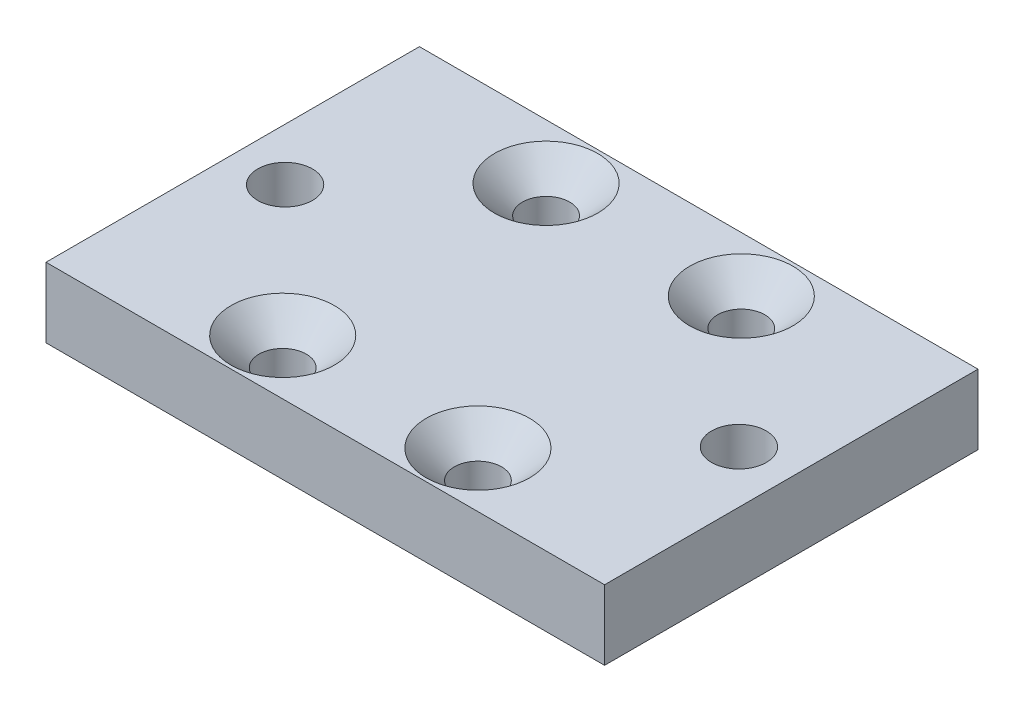
SolidWorks part; units mm, degrees
ref_plane "Front Plane" through (0, 0, 0) normal (0, 0, 1) x (1, 0, 0)
ref_plane "Top Plane" through (0, 0, 0) normal (0, 1, 0) x (1, 0, 0)
ref_plane "Right Plane" through (0, 0, 0) normal (1, 0, 0) x (0, 0, -1)
sketch "Sketch1" plane through (0, 0, 0) normal (0, 1, 0) x (1, 0, 0)
  line L1 (0, 0) -> (50.8, 0)
  line L2 (0, 0) -> (0, 33.9598)
  line L3 (0, 33.9598) -> (50.8, 33.9598)
  line L4 (50.8, 0) -> (50.8, 33.9598)
  dimension "D1" = 33.9598
  dimension "D2" = 50.8
extrude "Boss-Extrude1" add sketch "Sketch1" along normal blind 6.35
sketch "Sketch2" plane through (0, 6.35, 0) normal (0, 1, 0) x (1, 0, 0)
  line L0 (16.5227, 28.956) -> (0, 28.956) construction
  line L1 (0, 33.9598) -> (0, 0) construction
  line L2 (16.5227, 5.0038) -> (0, 5.0038) construction
  line L3 (16.5227, 5.0038) -> (16.5227, 0) construction
  line L4 (0, 0) -> (50.8, 0) construction
  line L5 (16.5227, 28.956) -> (16.5227, 33.9598) construction
  line L6 (50.8, 33.9598) -> (0, 33.9598) construction
  line L7 (34.2773, 28.956) -> (34.2773, 33.9598) construction
  line L8 (34.2773, 28.956) -> (50.8, 28.956) construction
  line L9 (50.8, 0) -> (50.8, 33.9598) construction
  line L10 (34.2773, 5.0038) -> (50.8, 5.0038) construction
  line L11 (34.2773, 5.0038) -> (34.2773, 0) construction
  line L12 (16.5227, 27.051) -> (16.5227, 6.9088) construction
  line L13 (32.3723, 28.956) -> (18.4277, 28.956) construction
  circle A0 centre (16.5227, 28.956) radius 1.905
  circle A1 centre (16.5227, 5.0038) radius 1.905
  circle A2 centre (34.2773, 28.956) radius 1.905
  circle A3 centre (34.2773, 5.0038) radius 1.905
  dimension "D3" = 3.81
  dimension "D1" = 23.9522
  dimension "D2" = 17.7546
extrude "through to bearing block" cut sketch "Sketch2" against normal through all
sketch "Sketch3" plane through (0, 6.35, 0) normal (0, 1, 0) x (1, 0, 0)
  line L0 (0, 16.9799) -> (4.7625, 16.9799) construction
  line L1 (0, 33.9598) -> (0, 0) construction
  line L2 (50.8, 16.9799) -> (46.0375, 16.9799) construction
  line L3 (50.8, 0) -> (50.8, 33.9598) construction
  circle A0 centre (4.7625, 16.9799) radius 2.4892
  circle A1 centre (46.0375, 16.9799) radius 2.4892
  dimension "D2" = 4.9784
  dimension "D1" = 4.7625
extrude "through to tnut" cut sketch "Sketch3" against normal through all
ref_plane "Plane1" through (0, 0, -28.956) normal (0, 0, -1) x (-1, 0, 0)
ref_plane "Plane2" through (25.4, 0, 0) normal (1, 0, 0) x (0, 0, -1)
ref_plane "Plane3" through (0, 0, -16.9799) normal (0, 0, -1) x (-1, 0, 0)
hole_wizard "CSK for M4 Flat Head Machine Screw1" positions "Sketch5" profile "Sketch6" countersink size "M4" standard "ANSI Metric" end condition through all
sketch "Sketch5" plane through (0, 6.35, 0) normal (0, 1, 0) x (1, 0, 0)
  point P0 (16.5227, 28.956)
  point P3 (16.5227, 5.0038)
  point P6 (34.2773, 5.0038)
  point P9 (34.2773, 28.956)
sketch "Sketch6" plane through (16.5227, 6.35, -28.956) normal (1, 0, 0) x (0, 0, 1)
  line L0 (0, 0) -> (0, 6.35)
  line L1 (0, 6.35) -> (2.15, 6.35)
  line L2 (2.15, 6.35) -> (2.15, 2.55)
  line L3 (2.15, 2.55) -> (4.7, 0)
  line L5 (4.7, 0) -> (0, 0)
  line L6 (-2.15, 2.55) -> (-4.7, 0) construction
  line L11 (0, -6.35) -> (0, 107.95) construction
  dimension "Thru Hole Dia." = 4.3
  dimension "Thru Hole Depth" = 6.35
  dimension "Near C'Sink Dia." = 9.4
  dimension "Near C'Sink Angle" = 90
